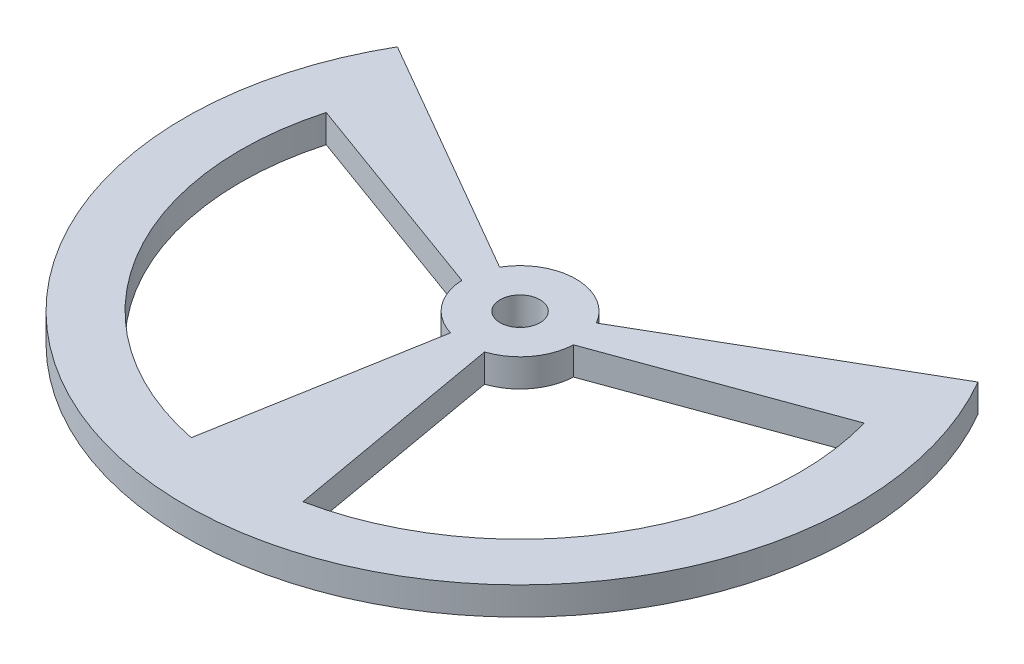
SolidWorks part; units mm, degrees
ref_plane "Front" through (0, 0, 0) normal (0, 0, 1) x (1, 0, 0)
ref_plane "Top" through (0, 0, 0) normal (0, 1, 0) x (1, 0, 0)
ref_plane "Right" through (0, 0, 0) normal (1, 0, 0) x (0, 0, -1)
sketch "Sketch1" plane through (0, 0, 0) normal (0, 1, 0) x (1, 0, 0)
  line L0 (0, 0) -> (0, 117.8577) construction
  line L1 (-108.7567, 0) -> (102.6894, 0) construction
  line L2 (-36.8113, 21.253) -> (-170.9029, 98.6708) construction
  line L3 (36.8113, 21.253) -> (160.5473, 92.6921) construction
  line L4 (-131.9823, 76.2) -> (-21.997, 12.7)
  line L5 (21.997, 12.7) -> (131.9823, 76.2)
  arc A0 (131.9823, 76.2) -> (-131.9823, 76.2) centre (0, 0) cw
  arc A1 (-21.997, 12.7) -> (21.997, 12.7) centre (0, 0) cw
  dimension "D1" = 152.4
  dimension "D2" = 25.4
  dimension "D3" = 240
extrude "Extrude1" add sketch "Sketch1" along normal blind 12.7
sketch "Sketch2" plane through (0, 12.7, 0) normal (0, 1, 0) x (1, 0, 0)
  line L0 (0, 116.8924) -> (0, -192.7247) construction
  line L1 (25.1847, -1.0964) -> (-209.1735, -1.0964) construction
  line L2 (-122.3125, 34.1855) -> (-25.3763, -1.0964)
  line L3 (-24.9581, -124.5235) -> (-7.2915, -24.3309)
  line L4 (25.3763, -1.0964) -> (122.3125, 34.1855)
  line L5 (7.9655, -24.1187) -> (25.645, -124.3838)
  line L7 (131.9823, 76.2) -> (21.997, 12.7) construction
  arc A0 (-122.3125, 34.1855) -> (-24.9581, -124.5235) centre (0, 0) ccw
  arc A1 (-25.3763, -1.0964) -> (-7.2915, -24.3309) centre (0, 0) ccw
  arc A2 (7.9655, -24.1187) -> (25.3763, -1.0964) centre (0, 0) ccw
  arc A3 (25.645, -124.3838) -> (122.3125, 34.1855) centre (0, 0) ccw
  dimension "D1" = 127
  dimension "D2" = 25.4
  dimension "D3" = 25.4
  dimension "D4" = 127
  dimension "D5" = 100
  dimension "D6" = 100
  dimension "D7" = 20
  dimension "D8" = 10
extrude "Extrude2" cut sketch "Sketch2" against normal through all
sketch "Sketch8" plane through (0, 0, 0) normal (0, -1, 0) x (1, 0, 0)
  circle A0 centre (0, 0) radius 9.0776
extrude "Extrude3" cut sketch "Sketch8" against normal through all
